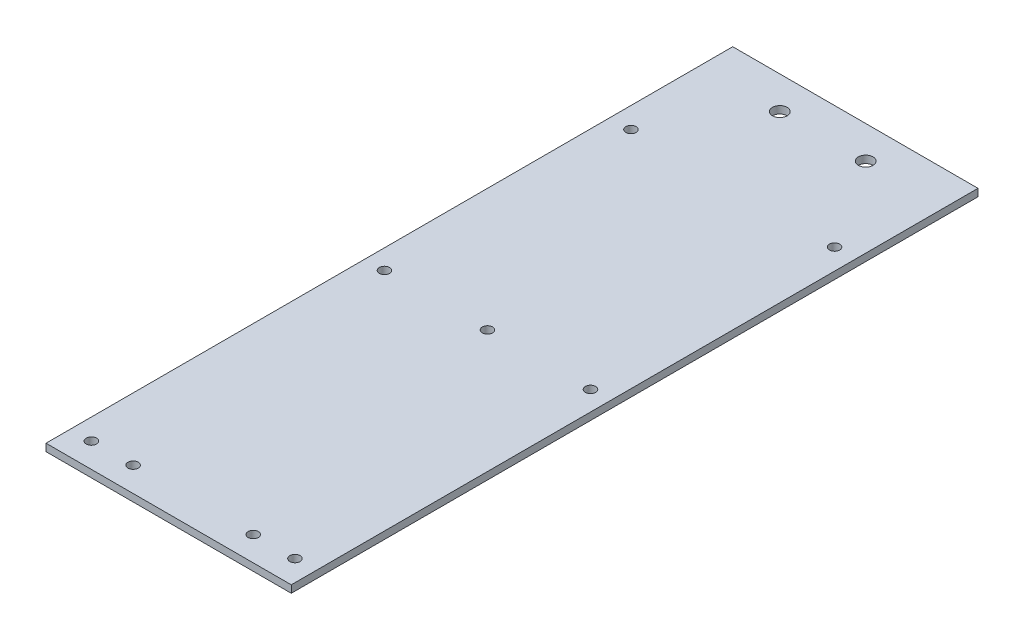
SolidWorks part; units mm, degrees
ref_plane "Front Plane" through (0, 0, 0) normal (0, 0, 1) x (1, 0, 0)
ref_plane "Top Plane" through (0, 0, 0) normal (0, 1, 0) x (1, 0, 0)
ref_plane "Right Plane" through (0, 0, 0) normal (1, 0, 0) x (0, 0, -1)
sketch "Sketch1" plane through (0, 0, 0) normal (0, 1, 0) x (1, 0, 0)
  line L1 (-50, 60) -> (50, 60)
  line L2 (-50, 60) -> (-50, -60)
  line L3 (-50, -60) -> (50, -60)
  line L4 (50, 60) -> (50, -60)
  line L5 (-50, 60) -> (50, -60) construction
  line L6 (-50, -60) -> (50, 60) construction
  line L7 (71.831, 0) -> (-33.8294, 0) construction
  line L8 (0, 117.1606) -> (0, -73.5833) construction
  circle A1 centre (41.5, -50) radius 2.1
  circle A2 centre (-41.5, -50) radius 2.1
  circle A4 centre (-42, 70) radius 2.1
  circle A5 centre (0, 70) radius 2.1
  circle A6 centre (42, 70) radius 2.1
  point P0 (0, 0)
  dimension "D3" = 130
  dimension "D8" = 4.2
  dimension "D1" = 100
  dimension "D2" = 120
  dimension "D6" = 60
  dimension "D7" = 50
extrude "Boss-Extrude1" add sketch "Sketch1" along normal blind 3
sketch "Sketch2" plane through (0, 0, 0) normal (0, -1, 0) x (1, 0, 0)
  line L0 (-50, -60) -> (-50, 60) construction
  line L1 (-50, 60) -> (50, 60) construction
  circle A2 centre (24.5, 50) radius 2.1
  circle A3 centre (-24.5, 50) radius 2.1
  dimension "D1" = 25.5
  dimension "D2" = 10
  dimension "D3" = 49
  dimension "D4" = 4.2
extrude "Cut-Extrude1" cut sketch "Sketch2" against normal blind 10
sketch "Sketch3" plane through (0, 0, -60) normal (0, 0, -1) x (-1, 0, 0)
  line L1 (50, 0) -> (-50, 0)
  line L2 (50, 0) -> (50, 3)
  line L3 (50, 3) -> (-50, 3)
  line L4 (-50, 0) -> (-50, 3)
extrude "Boss-Extrude2" add sketch "Sketch3" along normal blind 160
sketch "Sketch4" plane through (0, 0, 0) normal (0, -1, 0) x (1, 0, 0)
  line L0 (50, 60) -> (50, -220) construction
  line L1 (-50, -220) -> (-50, 60) construction
  line L3 (50, -220) -> (-50, -220) construction
  circle A0 centre (17.5, -206.7) radius 3
  circle A1 centre (-17.5, -206.7) radius 3
  circle A2 centre (-41.5, -170) radius 2.1
  circle A5 centre (41.5, -170) radius 2.1
  dimension "D1" = 4.2
  dimension "D2" = 6
  dimension "D5" = 50
  dimension "D6" = 32.5
  dimension "D7" = 32.5
  dimension "D8" = 13.3
  dimension "D3" = 8.5
  dimension "D4" = 8.5
extrude "Cut-Extrude2" cut sketch "Sketch4" against normal blind 160
sketch "Sketch5" plane through (0, 0, 0) normal (0, -1, 0) x (1, 0, 0)
  circle A0 centre (-42, -70) radius 2.1
  circle A1 centre (0, -70) radius 2.1
  circle A2 centre (42, -70) radius 2.1
  dimension "D1" = 4.2
extrude "Cut-Extrude3" cut sketch "Sketch5" against normal blind 10
